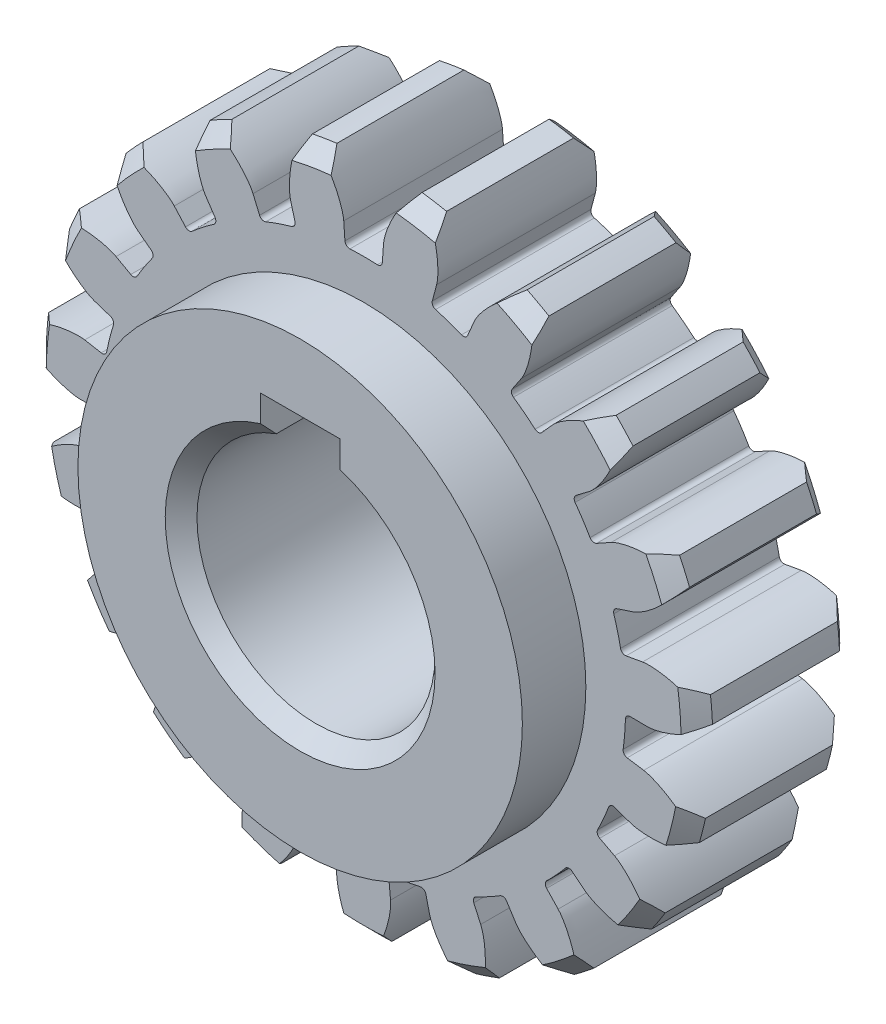
SolidWorks part; units mm, degrees
ref_plane "中间平面" through (0, 0, 0) normal (0, 0, 1) x (1, 0, 0)
ref_plane "上视基准面" through (0, 0, 0) normal (0, 1, 0) x (1, 0, 0)
ref_plane "右视基准面" through (0, 0, 0) normal (1, 0, 0) x (0, 0, -1)
sketch "直齿轮" plane through (0, 0, 0) normal (0, 0, 1) x (1, 0, 0)
  line L0 (0, 0) -> (-1.569, 18.9351) construction
  line L2 (-1.2527, 17.8102) -> (0, 0)
  line L3 (0, 0) -> (0, 52) construction
  line L4 (1.569, 18.9351) -> (0, 0) construction
  line L6 (0, 0) -> (1.2527, 17.8102)
  circle A0 centre (0, 0) radius 17.8542
  circle A1 centre (0, 0) radius 16.5
  arc A2 (1.569, 18.9351) -> (-1.569, 18.9351) centre (0, 0) ccw
  circle A3 centre (0, 0) radius 21
  spline S0 degree 4 poles (-1.2527, 17.8102) (-1.2551, 17.844) (-1.262, 17.9116) (-1.2839, 18.0457) (-1.3413, 18.2977) (-1.4438, 18.6296) (-1.622, 19.0817) (-1.8826, 19.6118) (-2.3513, 20.4075) (-3.1231, 21.4382) (-4.3729, 22.7339) (-6.2092, 24.1399) (-8.4273, 25.3786) (-10.9784, 26.3705) (-13.631, 27.0391) (-16.3413, 27.4039) (-19.2093, 27.4873) (-22.7524, 27.2198) (-26.9082, 26.3611) (-31.5415, 24.6687) (-36.3355, 22.0161) (-40.1513, 19.1175) (-43.1167, 16.2849) (-45.3725, 13.7225) (-47.044, 11.5624) (-48.5794, 9.3043) (-49.9762, 6.957) (-51.5471, 3.9273) (-53.1493, 0.1524) (-54.6038, -4.4037) (-55.4938, -8.7622) (-55.9171, -12.1429) (-56.0926, -14.5356) (-56.1598, -15.8727) (-56.1874, -17.1727) (-56.193, -18.1918) (-56.1725, -19.2684) (-56.1556, -19.8342) (-56.127, -20.5237) (-56.0985, -21.0714) (-56.0563, -21.7541) (-55.9946, -22.5814) (-55.9073, -23.5387) (-55.7864, -24.635) (-55.6447, -25.7262) (-55.4822, -26.8163) (-55.345, -27.6303) (-55.2467, -28.1725) (-55.1958, -28.443) knots 0 0 0 0 0 0.001401 0.002802 0.005604 0.010661 0.015718 0.022839 0.02996 0.048734 0.068727 0.096889 0.125051 0.153212 0.181374 0.209535 0.237696 0.271429 0.327752 0.384075 0.440398 0.496721 0.524883 0.553044 0.581206 0.609367 0.637529 0.66569 0.722013 0.778336 0.834659 0.84874 0.86282 0.876901 0.890982 0.900036 0.909091 0.914773 0.920455 0.926136 0.931818 0.943182 0.954545 0.965909 0.977273 0.988636 1 1 1 1 1 construction
  spline S1 degree 4 poles (-1.2527, 17.8102) (-1.2551, 17.844) (-1.262, 17.9116) (-1.2839, 18.0457) (-1.3413, 18.2977) (-1.4438, 18.6296) (-1.622, 19.0817) (-1.8826, 19.6118) (-2.3513, 20.4075) (-3.1231, 21.4382) (-4.3729, 22.7339) (-6.2092, 24.1399) (-8.4273, 25.3786) (-10.9784, 26.3705) (-13.631, 27.0391) (-16.3413, 27.4039) (-19.2093, 27.4873) (-22.7524, 27.2198) (-26.9082, 26.3611) (-31.5415, 24.6687) (-36.3355, 22.0161) (-40.1513, 19.1175) (-43.1167, 16.2849) (-45.3725, 13.7225) (-47.044, 11.5624) (-48.5794, 9.3043) (-49.9762, 6.957) (-51.5471, 3.9273) (-53.1493, 0.1524) (-54.6038, -4.4037) (-55.4938, -8.7622) (-55.9171, -12.1429) (-56.0926, -14.5356) (-56.1598, -15.8727) (-56.1874, -17.1727) (-56.193, -18.1918) (-56.1756, -19.1069) (-56.1653, -19.4945) (-56.1589, -19.6938) knots 0 0 0 0 0 0.001401 0.002802 0.005604 0.010661 0.015718 0.022839 0.02996 0.048734 0.068727 0.096889 0.125051 0.153212 0.181374 0.209535 0.237696 0.271429 0.327752 0.384075 0.440398 0.496721 0.524883 0.553044 0.581206 0.609367 0.637529 0.66569 0.722013 0.778336 0.834659 0.84874 0.86282 0.876901 0.890982 0.900036 0.909091 0.909091 0.909091 0.909091 0.909091
  spline S2 degree 4 poles (1.2527, 17.8102) (1.2551, 17.844) (1.262, 17.9116) (1.2839, 18.0457) (1.3413, 18.2977) (1.4438, 18.6296) (1.622, 19.0817) (1.8826, 19.6118) (2.3513, 20.4075) (3.1231, 21.4382) (4.3729, 22.7339) (6.2092, 24.1399) (8.4273, 25.3786) (10.9784, 26.3705) (13.631, 27.0391) (16.3413, 27.4039) (19.2093, 27.4873) (22.7524, 27.2198) (26.9082, 26.3611) (31.5415, 24.6687) (36.3355, 22.0161) (40.1513, 19.1175) (43.1167, 16.2849) (45.3725, 13.7225) (47.044, 11.5624) (48.5794, 9.3043) (49.9762, 6.957) (51.5471, 3.9273) (53.1493, 0.1524) (54.6038, -4.4037) (55.4938, -8.7622) (55.9171, -12.1429) (56.0926, -14.5356) (56.1598, -15.8727) (56.1874, -17.1727) (56.193, -18.1918) (56.1725, -19.2684) (56.1556, -19.8342) (56.127, -20.5237) (56.0985, -21.0714) (56.0563, -21.7541) (55.9946, -22.5814) (55.9073, -23.5387) (55.7864, -24.635) (55.6447, -25.7262) (55.4822, -26.8163) (55.345, -27.6303) (55.2467, -28.1725) (55.1958, -28.443) knots 0 0 0 0 0 0.001401 0.002802 0.005604 0.010661 0.015718 0.022839 0.02996 0.048734 0.068727 0.096889 0.125051 0.153212 0.181374 0.209535 0.237696 0.271429 0.327752 0.384075 0.440398 0.496721 0.524883 0.553044 0.581206 0.609367 0.637529 0.66569 0.722013 0.778336 0.834659 0.84874 0.86282 0.876901 0.890982 0.900036 0.909091 0.914773 0.920455 0.926136 0.931818 0.943182 0.954545 0.965909 0.977273 0.988636 1 1 1 1 1 construction
  spline S3 degree 4 poles (1.2527, 17.8102) (1.2551, 17.844) (1.262, 17.9116) (1.2839, 18.0457) (1.3413, 18.2977) (1.4438, 18.6296) (1.622, 19.0817) (1.8826, 19.6118) (2.3513, 20.4075) (3.1231, 21.4382) (4.3729, 22.7339) (6.2092, 24.1399) (8.4273, 25.3786) (10.9784, 26.3705) (13.631, 27.0391) (16.3413, 27.4039) (19.2093, 27.4873) (22.7524, 27.2198) (26.9082, 26.3611) (31.5415, 24.6687) (36.3355, 22.0161) (40.1513, 19.1175) (43.1167, 16.2849) (45.3725, 13.7225) (47.044, 11.5624) (48.5794, 9.3043) (49.9762, 6.957) (51.5471, 3.9273) (53.1493, 0.1524) (54.6038, -4.4037) (55.4938, -8.7622) (55.9171, -12.1429) (56.0926, -14.5356) (56.1598, -15.8727) (56.1874, -17.1727) (56.193, -18.1918) (56.1756, -19.1069) (56.1653, -19.4945) (56.1589, -19.6938) knots 0 0 0 0 0 0.001401 0.002802 0.005604 0.010661 0.015718 0.022839 0.02996 0.048734 0.068727 0.096889 0.125051 0.153212 0.181374 0.209535 0.237696 0.271429 0.327752 0.384075 0.440398 0.496721 0.524883 0.553044 0.581206 0.609367 0.637529 0.66569 0.722013 0.778336 0.834659 0.84874 0.86282 0.876901 0.890982 0.900036 0.909091 0.909091 0.909091 0.909091 0.909091
  dimension "基圆直径" = 35.7083
  dimension "齿根圆" = 33
  dimension "分度圆" = 38
  dimension "齿顶圆" = 42
  dimension "D1" = 3.1416
sketch "圆" plane through (0, 0, 0) normal (0, 0, 1) x (1, 0, 0)
  circle A0 centre (0, 0) radius 21 construction
  circle A1 centre (0, 0) radius 21
extrude "毛胚" add sketch "圆" along normal mid plane 10
chamfer "轮齿倒角" distance 1 angle 45 2 edges at (21, 0, -5) (21, 0, 5)
sketch "齿形" plane through (0, 0, 0) normal (0, 0, 1) x (1, 0, 0)
  line L4 (0, 0) -> (1.2527, 17.8102) construction
  line L5 (-1.2527, 17.8102) -> (0, 0) construction
  line L6 (0, 0) -> (1.2527, 17.8102)
  line L7 (-1.2527, 17.8102) -> (0, 0)
  circle A4 centre (0, 0) radius 16.5 construction
  circle A5 centre (0, 0) radius 21 construction
  circle A6 centre (0, 0) radius 16.5
  circle A7 centre (0, 0) radius 21
  spline S1 degree 4 poles (-998.091, 43.7983) (30.746, 11.7394) (1.8294, 14.6629) (0.9419, 16.5452) (1.3413, 18.2977) (1.4438, 18.6296) (1.622, 19.0817) (1.8826, 19.6118) (2.3513, 20.4075) (3.1231, 21.4382) (4.3729, 22.7339) (6.2092, 24.1399) (8.4273, 25.3786) (10.9784, 26.3705) (13.631, 27.0391) (16.3413, 27.4039) (19.2093, 27.4873) (22.7524, 27.2198) (26.9082, 26.3611) (31.5415, 24.6687) (36.3355, 22.0161) (40.1513, 19.1175) (43.1167, 16.2849) (45.3725, 13.7225) (47.044, 11.5624) (48.5794, 9.3043) (49.9762, 6.957) (51.5471, 3.9273) (53.1493, 0.1524) (54.6038, -4.4037) (55.4938, -8.7622) (55.9171, -12.1429) (56.0926, -14.5356) (56.1598, -15.8727) (56.1874, -17.1727) (56.2046, -20.3249) (55.8786, -26.481) (56.9168, 14.6594) (23.0461, -1019.0526) knots -0.063477 -0.063477 -0.063477 -0.063477 -0.063477 0.001401 0.002802 0.005604 0.010661 0.015718 0.022839 0.02996 0.048734 0.068727 0.096889 0.125051 0.153212 0.181374 0.209535 0.237696 0.271429 0.327752 0.384075 0.440398 0.496721 0.524883 0.553044 0.581206 0.609367 0.637529 0.66569 0.722013 0.778336 0.834659 0.84874 0.86282 0.876901 0.890982 0.900036 1.00595 1.00595 1.00595 1.00595 1.00595 only from (1.2527, 17.8102) to (56.1589, -19.6938) construction
  spline S3 degree 4 poles (998.091, 43.7983) (-30.746, 11.7394) (-1.8294, 14.6629) (-0.9419, 16.5452) (-1.3413, 18.2977) (-1.4438, 18.6296) (-1.622, 19.0817) (-1.8826, 19.6118) (-2.3513, 20.4075) (-3.1231, 21.4382) (-4.3729, 22.7339) (-6.2092, 24.1399) (-8.4273, 25.3786) (-10.9784, 26.3705) (-13.631, 27.0391) (-16.3413, 27.4039) (-19.2093, 27.4873) (-22.7524, 27.2198) (-26.9082, 26.3611) (-31.5415, 24.6687) (-36.3355, 22.0161) (-40.1513, 19.1175) (-43.1167, 16.2849) (-45.3725, 13.7225) (-47.044, 11.5624) (-48.5794, 9.3043) (-49.9762, 6.957) (-51.5471, 3.9273) (-53.1493, 0.1524) (-54.6038, -4.4037) (-55.4938, -8.7622) (-55.9171, -12.1429) (-56.0926, -14.5356) (-56.1598, -15.8727) (-56.1874, -17.1727) (-56.2046, -20.3249) (-55.8786, -26.481) (-56.9168, 14.6594) (-23.0461, -1019.0526) knots -0.063477 -0.063477 -0.063477 -0.063477 -0.063477 0.001401 0.002802 0.005604 0.010661 0.015718 0.022839 0.02996 0.048734 0.068727 0.096889 0.125051 0.153212 0.181374 0.209535 0.237696 0.271429 0.327752 0.384075 0.440398 0.496721 0.524883 0.553044 0.581206 0.609367 0.637529 0.66569 0.722013 0.778336 0.834659 0.84874 0.86282 0.876901 0.890982 0.900036 1.00595 1.00595 1.00595 1.00595 1.00595 only from (-1.2527, 17.8102) to (-56.1589, -19.6938) construction
  spline S4 degree 4 poles (1.2527, 17.8102) (1.2551, 17.844) (1.262, 17.9116) (1.2839, 18.0457) (1.3413, 18.2977) (1.4438, 18.6296) (1.622, 19.0817) (1.8826, 19.6118) (2.3513, 20.4075) (3.1231, 21.4382) (4.3729, 22.7339) (6.2092, 24.1399) (8.4273, 25.3786) (10.9784, 26.3705) (13.631, 27.0391) (16.3413, 27.4039) (19.2093, 27.4873) (22.7524, 27.2198) (26.9082, 26.3611) (31.5415, 24.6687) (36.3355, 22.0161) (40.1513, 19.1175) (43.1167, 16.2849) (45.3725, 13.7225) (47.044, 11.5624) (48.5794, 9.3043) (49.9762, 6.957) (51.5471, 3.9273) (53.1493, 0.1524) (54.6038, -4.4037) (55.4938, -8.7622) (55.9171, -12.1429) (56.0926, -14.5356) (56.1598, -15.8727) (56.1874, -17.1727) (56.193, -18.1918) (56.1756, -19.1069) (56.1653, -19.4945) (56.1589, -19.6938) knots 0 0 0 0 0 0.001401 0.002802 0.005604 0.010661 0.015718 0.022839 0.02996 0.048734 0.068727 0.096889 0.125051 0.153212 0.181374 0.209535 0.237696 0.271429 0.327752 0.384075 0.440398 0.496721 0.524883 0.553044 0.581206 0.609367 0.637529 0.66569 0.722013 0.778336 0.834659 0.84874 0.86282 0.876901 0.890982 0.900036 0.909091 0.909091 0.909091 0.909091 0.909091
  spline S5 degree 4 poles (-1.2527, 17.8102) (-1.2551, 17.844) (-1.262, 17.9116) (-1.2839, 18.0457) (-1.3413, 18.2977) (-1.4438, 18.6296) (-1.622, 19.0817) (-1.8826, 19.6118) (-2.3513, 20.4075) (-3.1231, 21.4382) (-4.3729, 22.7339) (-6.2092, 24.1399) (-8.4273, 25.3786) (-10.9784, 26.3705) (-13.631, 27.0391) (-16.3413, 27.4039) (-19.2093, 27.4873) (-22.7524, 27.2198) (-26.9082, 26.3611) (-31.5415, 24.6687) (-36.3355, 22.0161) (-40.1513, 19.1175) (-43.1167, 16.2849) (-45.3725, 13.7225) (-47.044, 11.5624) (-48.5794, 9.3043) (-49.9762, 6.957) (-51.5471, 3.9273) (-53.1493, 0.1524) (-54.6038, -4.4037) (-55.4938, -8.7622) (-55.9171, -12.1429) (-56.0926, -14.5356) (-56.1598, -15.8727) (-56.1874, -17.1727) (-56.193, -18.1918) (-56.1756, -19.1069) (-56.1653, -19.4945) (-56.1589, -19.6938) knots 0 0 0 0 0 0.001401 0.002802 0.005604 0.010661 0.015718 0.022839 0.02996 0.048734 0.068727 0.096889 0.125051 0.153212 0.181374 0.209535 0.237696 0.271429 0.327752 0.384075 0.440398 0.496721 0.524883 0.553044 0.581206 0.609367 0.637529 0.66569 0.722013 0.778336 0.834659 0.84874 0.86282 0.876901 0.890982 0.900036 0.909091 0.909091 0.909091 0.909091 0.909091
extrude "插齿" cut sketch "齿形" against normal mid plane 10 contours S5 A6 S4 A7
fillet "圆角1" [suppressed] radius 0.3
pattern_circular "圆周阵列1" [suppressed] count 19 over 360
fillet "圆角2" radius 0.3 2 edges at (1.1577, 16.4593, 0) (-1.1577, 16.4593, 0)
pattern_circular "圆周阵列2" count 19 over 360 about axis through (0, 0, 5) along (0, 0, -1) of "圆角2", "插齿"
sketch "分度圆" plane through (0, 0, 0) normal (0, 0, 1) x (1, 0, 0)
  circle A0 centre (0, 0) radius 19 construction
  circle A1 centre (0, 0) radius 19 construction
sketch "草图1" plane through (0, 0, 5) normal (0, 0, 1) x (1, 0, 0)
  circle A0 centre (0, 0) radius 14
  dimension "D1" = 28
extrude "凸台-拉伸1" add sketch "草图1" along normal blind 4
sketch "草图2" plane through (0, 0, 9) normal (0, 0, 1) x (1, 0, 0)
  line L0 (2.5, 5.2) -> (2.5, 7.0711) construction
  line L1 (-2.5, 5.2) -> (2.5, 5.2) construction
  line L2 (-2.5, 7.0711) -> (-2.5, 9.8)
  line L3 (-2.5, 9.8) -> (2.5, 9.8)
  line L4 (2.5, 7.0711) -> (2.5, 9.8)
  line L5 (0, 7.5) -> (2.5, 9.8) construction
  line L6 (-2.5, 9.8) -> (0, 7.5) construction
  line L7 (0, 7.5) -> (2.5, 5.2) construction
  line L8 (-2.5, 5.2) -> (0, 7.5) construction
  line L9 (-2.5, 5.2) -> (-2.5, 7.0711) construction
  arc A0 (-2.5, 7.0711) -> (2.5, 7.0711) centre (0, 0) ccw
  arc A1 (0, 7.5) -> (-2.5, 7.0711) centre (0, 0) ccw construction
  arc A2 (2.5, 7.0711) -> (0, 7.5) centre (0, 0) ccw construction
  point P3 (0, 7.5)
  dimension "D1" = 15
  dimension "D2" = 5
  dimension "D3" = 17.3
extrude "切除-拉伸1" cut sketch "草图2" against normal through all
chamfer "倒角2" distance 1 angle 45 2 edges at (0, -7.5, -5) (0, -7.5, 9)
equation "\"m\"= 2'模数"
equation "\"z\" = 19'齿数"
equation "\"a\"= 20'压力角（常见为20°）"
equation "\"B\" = 10'齿宽"
equation "\"C1\"= 1'轮齿倒角（若设为0，则无倒角）"
equation "\"x\"= 0'变位系数（不懂勿动）"
equation "\"ha\"= 1'齿顶高系数（不懂勿动）"
equation "\"c\"= 0.25'顶隙系数（不懂勿动）"
equation "\"基圆直径@直齿轮\"= \"m\" * \"z\" * cos ( \"a\" )"
equation "\"齿根圆@直齿轮\" = \"m\" * ( \"z\" - 2 * ( \"ha\" - \"x\" + \"c\" ) )"
equation "\"分度圆@直齿轮\"=\"m\" * \"z\""
equation "\"齿顶圆@直齿轮\" = \"m\" * ( \"z\" + 2 * ( \"ha\" + \"x\" ) )"
equation "\"R\"= 0.3'齿根圆角"
equation "\"D1\"= \"R\""
equation "\"D1@毛胚\" = \"B\""
equation "\"D1@轮齿倒角\" = IIF ( \"C1\" > 0 , \"C1\" , 0.001 )"
equation "\"轮齿倒角\"= IIF ( \"C1\" > 0 , \"unsuppressed\" , \"suppressed\" )"
equation "\"D1@插齿\" = \"B\""
equation "\"D1@圆周阵列1\" = \"z\""
equation "\"D1@直齿轮\"= \"m\" * ( pi / 2 ) - 2 * \"m\" * tan ( \"a\" ) * \"x\"'作者：机械菌-"
equation "\"D1@圆角1\"=\"R\""
equation "\"圆角1\" = IIF ( \"m\" * ( \"z\" - 2 * ( \"ha\" - \"x\" + \"c\" ) ) > \"m\" * \"z\" * cos ( \"a\" ) , \"unsuppressed\" , \"suppressed\" )"
equation "\"圆周阵列1\"= IIF ( \"m\" * ( \"z\" - 2 * ( \"ha\" - \"x\" + \"c\" ) ) > \"m\" * \"z\" * cos ( \"a\" ) , \"unsuppressed\" , \"suppressed\" )"
equation "\"D1@圆角2\"=\"R\""
equation "\"D1@圆周阵列2\" = \"z\""
equation "\"圆角2\" = IIF ( \"m\" * ( \"z\" - 2 * ( \"ha\" - \"x\" + \"c\" ) ) < \"m\" * \"z\" * cos ( \"a\" ) , \"unsuppressed\" , \"suppressed\" )"
equation "\"圆周阵列2\"= IIF ( \"m\" *  ( \"z\" - 2 *  ( \"ha\" - \"x\" + \"c\" )  )  < \"m\" * \"z\" * cos ( \"a\" )  ,  unsuppressed  ,  suppressed  ) "
